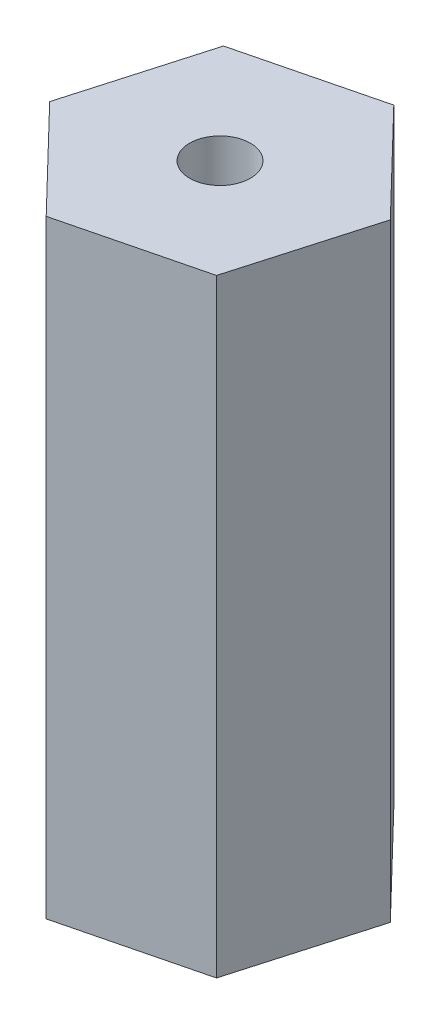
SolidWorks part; units mm, degrees
material "ABS"
ref_plane "Plano frontal" through (0, 0, 0) normal (0, 0, 1) x (1, 0, 0)
ref_plane "Plano superior" through (0, 0, 0) normal (0, 1, 0) x (1, 0, 0)
ref_plane "Plano direito" through (0, 0, 0) normal (1, 0, 0) x (0, 0, -1)
sketch "Esboço1" plane through (0, 0, 0) normal (0, 1, 0) x (1, 0, 0)
  line L1 (4.8123, -4.9842) -> (6.7226, 1.6755)
  line L2 (6.7226, 1.6755) -> (1.9103, 6.6596)
  line L3 (1.9103, 6.6596) -> (-4.8123, 4.9842)
  line L4 (-4.8123, 4.9842) -> (-6.7226, -1.6755)
  line L5 (-6.7226, -1.6755) -> (-1.9103, -6.6596)
  line L6 (-1.9103, -6.6596) -> (4.8123, -4.9842)
  circle A0 centre (0, 0) radius 6 construction
extrude "Ressalto-extrusão1" add sketch "Esboço1" along normal blind 30
sketch "Esboço2" plane through (0, 0, 0) normal (0, -1, 0) x (1, 0, 0)
  circle A0 centre (0, 0) radius 1.5
extrude "Corte-extrusão1" cut sketch "Esboço2" against normal blind 30
